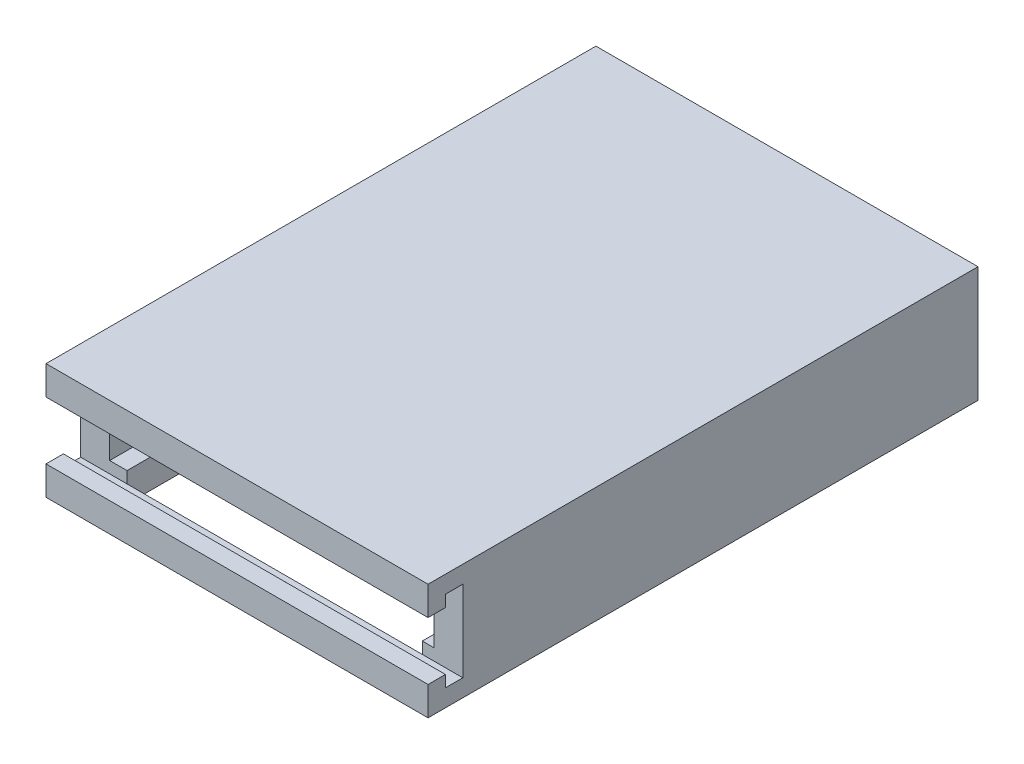
SolidWorks part; units mm, degrees
ref_plane "정면" through (0, 0, 0) normal (0, 0, 1) x (1, 0, 0)
ref_plane "윗면" through (0, 0, 0) normal (0, 1, 0) x (1, 0, 0)
ref_plane "우측면" through (0, 0, 0) normal (1, 0, 0) x (0, 0, -1)
sketch "스케치1" plane through (0, 0, 0) normal (0, 0, 1) x (1, 0, 0)
  line L1 (0, 0) -> (56, 0)
  line L2 (0, 0) -> (0, 10)
  line L3 (0, 10) -> (56, 10)
  line L4 (56, 0) -> (56, 10)
  line L5 (-5, 0) -> (61, 0)
  line L6 (-5, 0) -> (-5, 15)
  line L7 (-5, 15) -> (61, 15)
  line L8 (61, 0) -> (61, 15)
  point P9 (-5, 15)
  point P10 (0, 0)
  dimension "D1" = 56
  dimension "D2" = 10
  dimension "D3" = 5
  dimension "D4" = 5
  dimension "D5" = 15
extrude "보스-돌출1" add sketch "스케치1" along normal blind 84 contours L5 L8 L7 L6 L2 L3 L4
sketch "스케치2" plane through (0, 0, 0) normal (0, -1, 0) x (1, 0, 0)
  line L0 (0, 0) -> (56, 0) construction
  line L1 (-5, 84) -> (3, 84)
  line L2 (-5, 84) -> (-5, 0)
  line L3 (-5, 0) -> (3, 0)
  line L4 (3, 84) -> (3, 0)
  line L5 (0, 84) -> (56, 84) construction
  line L6 (61, 0) -> (54, 0)
  line L7 (61, 0) -> (61, 84)
  line L8 (61, 84) -> (54, 84)
  line L9 (54, 0) -> (54, 84)
  dimension "D1" = 7
  dimension "D2" = 8
extrude "보스-돌출2" add sketch "스케치2" along normal blind 5
sketch "스케치3" plane through (0, 0, 0) normal (0, 0, -1) x (-1, 0, 0)
  line L1 (-61, 15) -> (5, 15)
  line L2 (-61, 15) -> (-61, -5)
  line L3 (-61, -5) -> (5, -5)
  line L4 (5, 15) -> (5, -5)
extrude "보스-돌출3" add sketch "스케치3" along normal blind 5
sketch "스케치4" plane through (-5, 0, 0) normal (-1, 0, 0) x (0, 0, 1)
  line L0 (84, 15) -> (90, 15)
  line L1 (90, 15) -> (90, 10)
  line L2 (90, 10) -> (87, 10)
  line L3 (87, 10) -> (87, 12)
  line L4 (87, 12) -> (84, 12)
  line L5 (84, -5) -> (84, 15) construction
  line L6 (84, -5) -> (90, -5)
  line L7 (90, -5) -> (90, 0)
  line L8 (90, 0) -> (87, 0)
  line L9 (87, 0) -> (87, -2)
  line L10 (87, -2) -> (84, -2)
  line L11 (84, 15) -> (84, 12)
  line L12 (84, -2) -> (84, -5)
  dimension "D1" = 2
  dimension "D2" = 3
  dimension "D3" = 6
  dimension "D4" = 3
extrude "보스-돌출4" add sketch "스케치4" against normal up to vertex (66 mm away)
